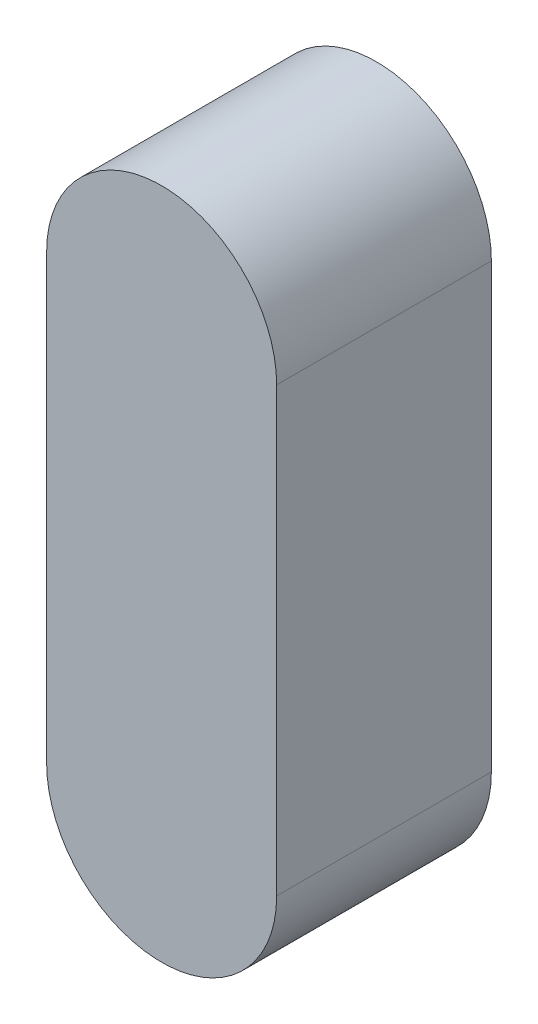
SolidWorks part; units mm, degrees
ref_plane "Front Plane" through (0, 0, 0) normal (0, 0, 1) x (1, 0, 0)
ref_plane "Top Plane" through (0, 0, 0) normal (0, 1, 0) x (1, 0, 0)
ref_plane "Right Plane" through (0, 0, 0) normal (1, 0, 0) x (0, 0, -1)
sketch "Stem Block Sketch" plane through (0, 0, 0) normal (0, 0, 1) x (1, 0, 0)
  line L0 (0, 0) -> (0, 267.978) construction
  line L1 (-69.6413, 0) -> (-69.6413, 267.978)
  line L2 (69.6413, 0) -> (69.6413, 267.978)
  arc A0 (-69.6413, 0) -> (69.6413, 0) centre (0, 0) ccw
  arc A1 (69.6413, 267.978) -> (-69.6413, 267.978) centre (0, 267.978) ccw
  point P3 (0, 133.989)
  dimension "D1" = 139.2826
extrude "Stem Block Extrude" add sketch "Stem Block Sketch" along normal offset from surface 10 and the other way offset from surface (65 mm away) 10
equation "\"D1@Stem Block Sketch\" = \"D1@Stem Block Sketch@Gripper Segment 01<1>.Part\" + 10mm"
